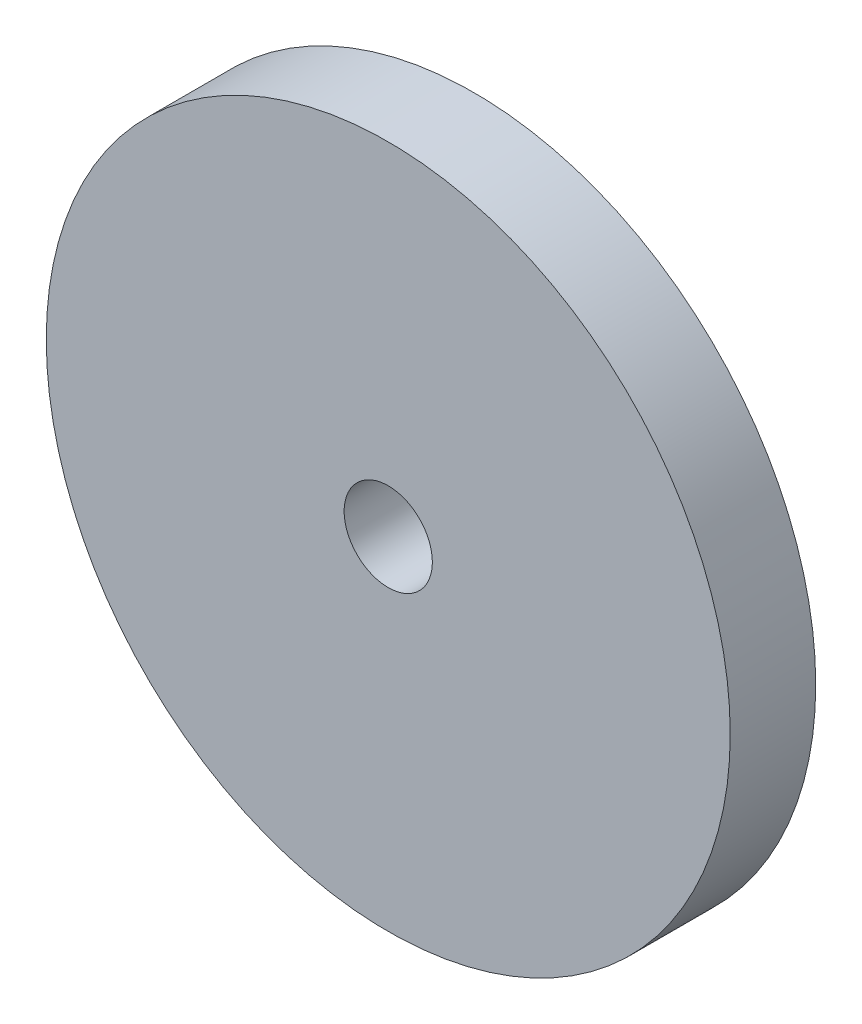
SolidWorks part; units mm, degrees
ref_plane "Front Plane" through (0, 0, 0) normal (0, 0, 1) x (1, 0, 0)
ref_plane "Top Plane" through (0, 0, 0) normal (0, 1, 0) x (1, 0, 0)
ref_plane "Right Plane" through (0, 0, 0) normal (1, 0, 0) x (0, 0, -1)
sketch "Sketch2" plane through (0, 0, 0) normal (0, 0, 1) x (1, 0, 0)
  circle A0 centre (0, 0) radius 25.4
  circle A1 centre (0, 0) radius 3.2766
  dimension "D1" = 50.8
  dimension "D2" = 6.5532
extrude "Boss-Extrude1" add sketch "Sketch2" along normal blind 6.35
